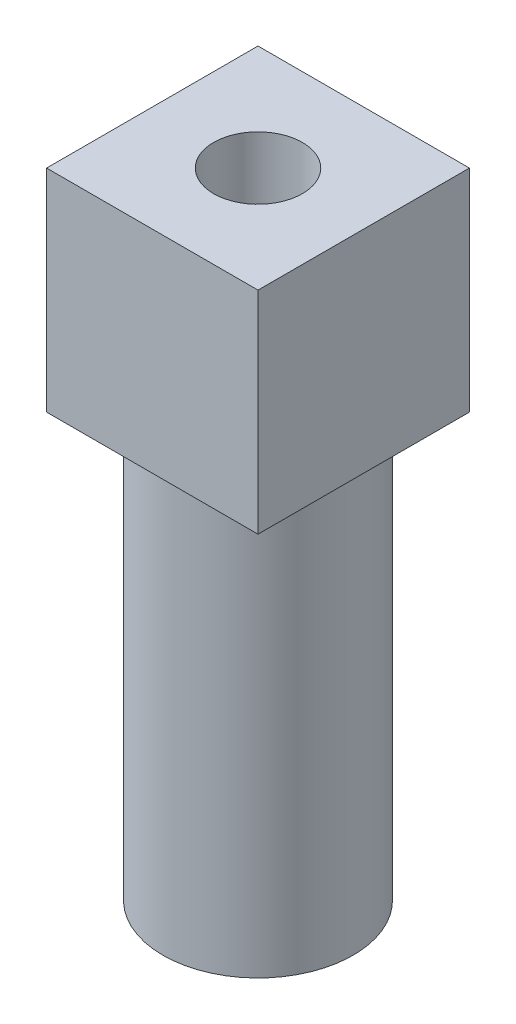
SolidWorks part; units mm, degrees
ref_plane "Ebene vorne" through (0, 0, 0) normal (0, 0, 1) x (1, 0, 0)
ref_plane "Ebene oben" through (0, 0, 0) normal (0, 1, 0) x (1, 0, 0)
ref_plane "Ebene rechts" through (0, 0, 0) normal (1, 0, 0) x (0, 0, -1)
sketch "Skizze1" plane through (0, 0, 0) normal (0, 0, 1) x (1, 0, 0)
  line L0 (0, 0) -> (4.5, 0)
  line L1 (4.5, 0) -> (4.5, 20)
  line L2 (0, 20) -> (4.5, 20)
  line L4 (0, -2.4593) -> (0, 22.5998) construction
  line L6 (0, 20) -> (0, 0)
  dimension "D1" = 4.5
  dimension "D2" = 20
revolve "Rotation1" add sketch "Skizze1" angle 360 about L4
sketch "Skizze5" plane through (0, 20, 0) normal (0, 1, 0) x (1, 0, 0)
  line L0 (0, 5) -> (0, -5) construction
  line L1 (-5, 5) -> (5, 5)
  line L2 (-5, 5) -> (-5, -5)
  line L3 (-5, -5) -> (5, -5)
  line L4 (5, 5) -> (5, -5)
  line L5 (5, 0) -> (-5, 0) construction
  dimension "D1" = 10
extrude "Aufsatz-Linear austragen1" add sketch "Skizze5" along normal blind 10
hole_wizard "M5 Gewindebohrung2" positions "Skizze6" profile "Skizze7" tap size "M5" standard "DIN" end condition through all
sketch "Skizze6" plane through (0, 30, 0) normal (0, 1, 0) x (1, 0, 0)
  point P0 (0, 0)
sketch "Skizze7" plane through (0, 30, 0) normal (1, 0, 0) x (0, 0, 1)
  line L0 (0, 0) -> (0, 30)
  line L1 (0, 30) -> (2.1, 30)
  line L2 (2.1, 30) -> (2.1, 0)
  line L5 (2.1, 0) -> (0, 0)
  line L11 (0, -6.35) -> (0, 107.95) construction
  dimension "Bohrerdurchmesser" = 4.2
  dimension "Bohrungstiefe" = 30
cosmetic thread "Bohrungsgewinde2" parameters "D2"=5
